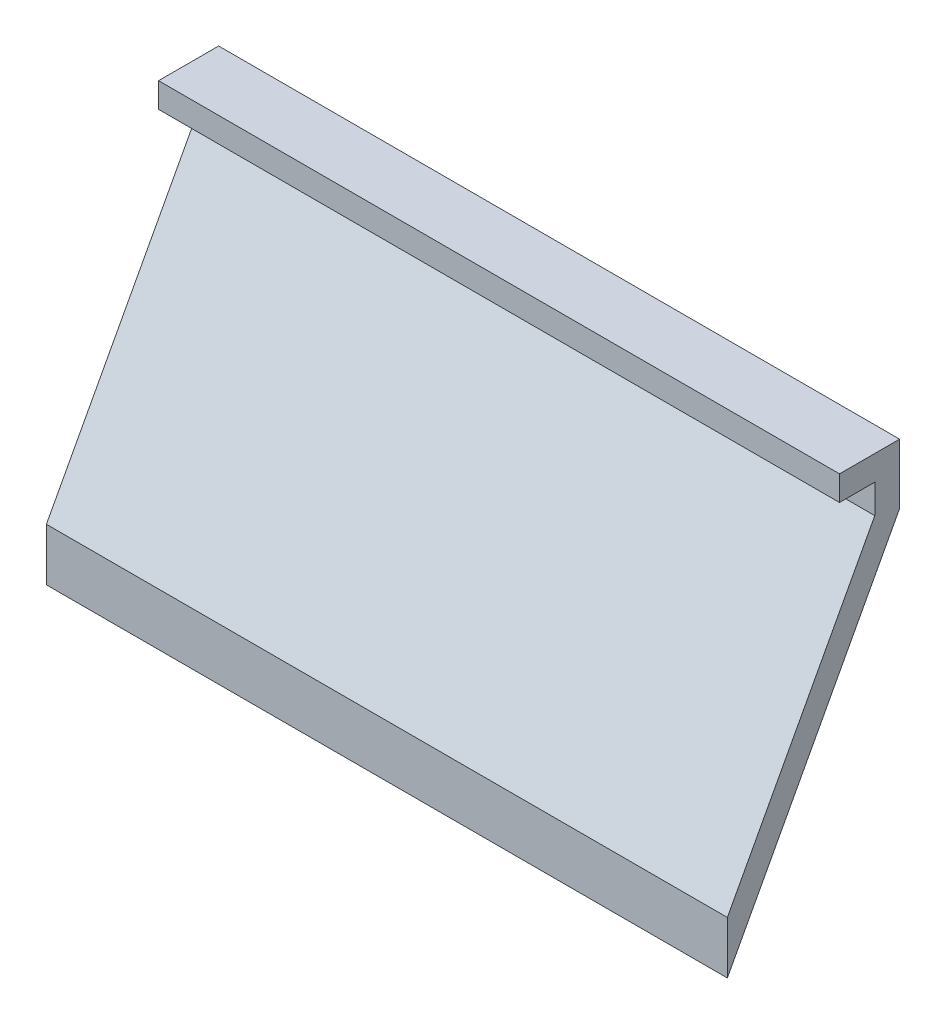
SolidWorks part; units mm, degrees
material "Acrylic (Medium-high impact)"
ref_plane "Front Plane" through (0, 0, 0) normal (0, 0, 1) x (1, 0, 0)
ref_plane "Top Plane" through (0, 0, 0) normal (0, 1, 0) x (1, 0, 0)
ref_plane "Right Plane" through (0, 0, 0) normal (1, 0, 0) x (0, 0, -1)
sketch "Sketch1" plane through (0, 0, 0) normal (1, 0, 0) x (0, 0, -1)
  line L7 (21.5, 55) -> (21.5, 40)
  line L8 (21.5, 40) -> (-21.5, -40)
  line L9 (-21.5, -40) -> (-21.5, -26.9044)
  line L10 (-21.5, -26.9044) -> (15.3, 41.5607)
  line L11 (15.3, 41.5607) -> (15.3, 48.8)
  line L14 (-21.5, 55) -> (-21.5, -40) construction
  line L15 (21.5, 55) -> (6.5, 55)
  line L16 (6.5, 55) -> (6.5, 48.8)
  line L17 (6.5, 48.8) -> (15.3, 48.8)
  line L18 (-21.5, 55) -> (6.5, 55) construction
  line L19 (15.3, 41.5607) -> (20.7611, 38.6253) construction
  line L20 (-21.5, -26.9044) -> (-16.0389, -29.8398) construction
  line L21 (-21.5, -40) -> (-26.9611, -37.0647) construction
  line L22 (-26.9611, -37.0647) -> (-21.5, -26.9044) construction
  line L23 (21.5, 40) -> (14.4611, 40) construction
  point P2 (0, 0)
  dimension "D1" = 6.2
  dimension "D2" = 43
  dimension "D3" = 6.2
  dimension "D4" = 95
  dimension "D5" = 6.2
  dimension "D6" = 15
  dimension "D7" = 61.742
  dimension "D8" = 61.742
extrude "Boss-Extrude1" add sketch "Sketch1" along normal mid plane 170
